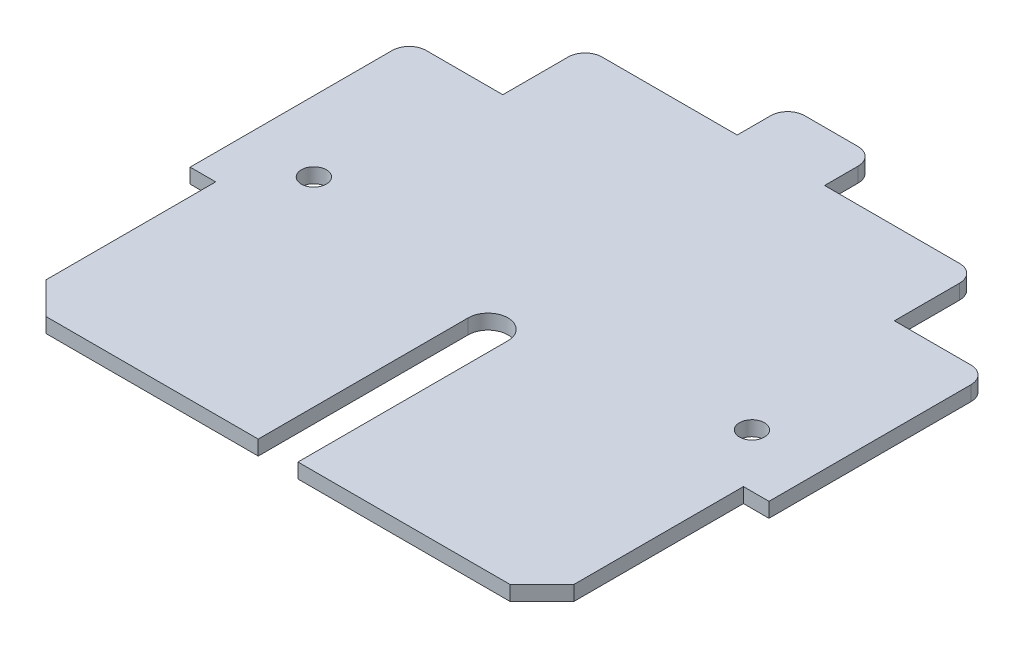
SolidWorks part; units mm, degrees
ref_plane "Front Plane" through (0, 0, 0) normal (0, 0, 1) x (1, 0, 0)
ref_plane "Top Plane" through (0, 0, 0) normal (0, 1, 0) x (1, 0, 0)
ref_plane "Right Plane" through (0, 0, 0) normal (1, 0, 0) x (0, 0, -1)
sketch "Sketch1" plane through (0, 0, 0) normal (0, 1, 0) x (1, 0, 0)
  line L0 (0, 42.7143) -> (0, -26.1949) construction
  line L1 (-27.0209, 0) -> (31.0327, 0) construction
  line L2 (20.45, -24.375) -> (23.25, -21.575)
  line L3 (-2.35, 24.375) -> (2.35, 24.375)
  line L4 (-25.5, 11.175) -> (-25.5, -6.625)
  line L5 (-20.45, -24.375) -> (-1.75, -24.375)
  line L6 (25.5, 11.175) -> (25.5, -6.625)
  line L7 (-17.25, 16.489) -> (22.918, -21.907) construction
  line L8 (-22.918, -21.907) -> (17.25, 16.489) construction
  line L9 (23.25, -21.575) -> (23.25, -8.875)
  line L10 (25.5, -6.625) -> (25.5, -24.375) construction
  line L11 (22.918, -21.907) -> (25.5, -24.375) construction
  line L12 (20.45, -24.375) -> (25.5, -24.375) construction
  line L13 (1.75, -24.375) -> (1.75, -5.875)
  line L14 (0, -24.375) -> (1.75, -24.375) construction
  line L15 (1.75, -24.375) -> (20.45, -24.375)
  line L16 (24, 12.675) -> (17.25, 12.675)
  line L17 (17.25, 12.675) -> (17.25, 18.425)
  line L18 (15.75, 19.925) -> (3.85, 19.925)
  line L19 (3.85, 19.925) -> (3.85, 22.875)
  line L20 (3.85, 24.375) -> (25.5, 24.375) construction
  line L21 (17.25, 16.489) -> (25.5, 24.375) construction
  line L22 (25.5, 24.375) -> (25.5, 12.675) construction
  line L23 (-1.75, -24.375) -> (-1.75, -5.875)
  line L24 (-20.45, -24.375) -> (-23.25, -21.575)
  line L25 (-23.25, -21.575) -> (-23.25, -8.875)
  line L26 (-24, 12.675) -> (-17.25, 12.675)
  line L27 (-17.25, 12.675) -> (-17.25, 18.425)
  line L28 (-15.75, 19.925) -> (-3.85, 19.925)
  line L29 (-3.85, 19.925) -> (-3.85, 22.875)
  line L30 (-1.75, -24.375) -> (0, -24.375) construction
  line L31 (-25.5, -6.625) -> (-25.5, -24.375) construction
  line L32 (-25.5, -24.375) -> (-22.918, -21.907) construction
  line L33 (-25.5, -24.375) -> (-20.45, -24.375) construction
  line L34 (-25.5, 24.375) -> (-25.5, 12.675) construction
  line L35 (-25.5, 24.375) -> (-17.25, 16.489) construction
  line L36 (-25.5, 24.375) -> (-3.85, 24.375) construction
  line L37 (20.4, -1.925) -> (20.4, -1.7597) construction
  line L38 (19.3, -0.825) -> (14.4085, -0.825) construction
  line L39 (23.25, -8.875) -> (23.25, -6.625)
  line L40 (23.25, -6.625) -> (25.5, -6.625)
  line L41 (-23.25, -6.625) -> (-23.25, -8.875)
  line L42 (-23.25, -6.625) -> (-25.5, -6.625)
  arc A0 (25.5, -6.625) -> (23.25, -8.875) centre (25.5, -8.875) ccw construction
  arc A1 (1.75, -5.875) -> (-1.75, -5.875) centre (0, -5.875) ccw
  arc A2 (-25.5, -6.625) -> (-23.25, -8.875) centre (-25.5, -8.875) cw construction
  circle A3 centre (19.3, -1.925) radius 1.1
  circle A4 centre (-19.3, -1.925) radius 1.1
  arc A5 (25.5, 11.175) -> (24, 12.675) centre (24, 11.175) ccw
  arc A6 (17.25, 18.425) -> (15.75, 19.925) centre (15.75, 18.425) ccw
  arc A7 (2.35, 24.375) -> (3.85, 22.875) centre (2.35, 22.875) cw
  arc A8 (-3.85, 22.875) -> (-2.35, 24.375) centre (-2.35, 22.875) cw
  arc A9 (-17.25, 18.425) -> (-15.75, 19.925) centre (-15.75, 18.425) cw
  arc A10 (-25.5, 11.175) -> (-24, 12.675) centre (-24, 11.175) cw
  point P5 (0, 0)
  point P55 (17.25, 19.925)
  point P64 (-17.25, 19.925)
  dimension "D3" = 17.75
  dimension "D8" = 18.5
  dimension "D13" = 5.1
  dimension "D15" = 2.2
  dimension "D16" = 1.5
  dimension "D1" = 48.75
  dimension "D2" = 51
  dimension "D4" = 2.25
  dimension "D5" = 2.8
  dimension "D6" = 45
  dimension "D7" = 21.5
  dimension "D9" = 19.3
  dimension "D10" = 8.25
  dimension "D11" = 7.25
  dimension "D12" = 7.7
  dimension "D14" = 13.5
extrude "Boss-Extrude1" add sketch "Sketch1" along normal mid plane 1.3
